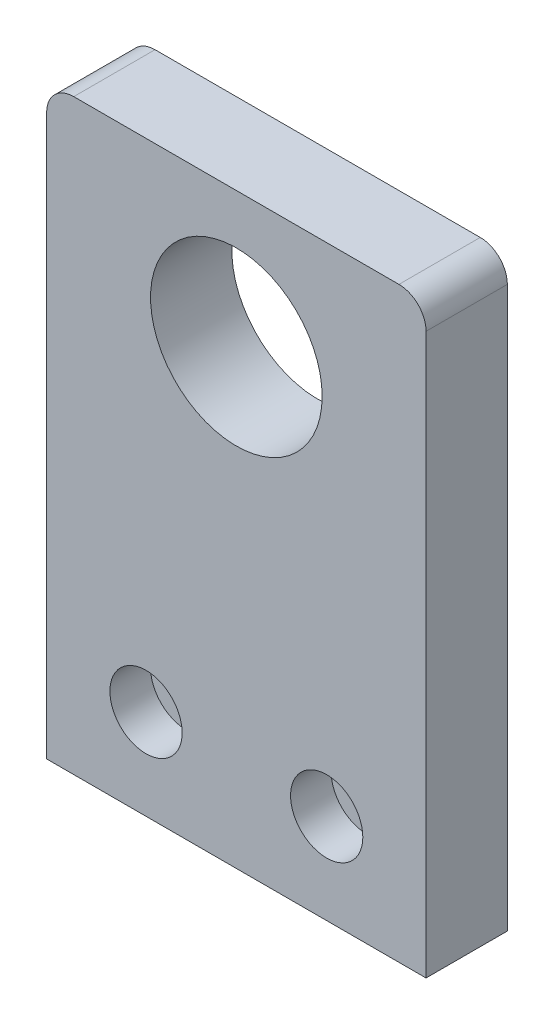
SolidWorks part; units mm, degrees
material "AISI 1035 Acero (SS)"
ref_plane "Alzado" through (0, 0, 0) normal (0, 0, 1) x (1, 0, 0)
ref_plane "Planta" through (0, 0, 0) normal (0, 1, 0) x (1, 0, 0)
ref_plane "Vista lateral" through (0, 0, 0) normal (1, 0, 0) x (0, 0, -1)
sketch "Croquis1" plane through (0, 0, 0) normal (0, 0, 1) x (1, 0, 0)
  line L1 (-18, 32.5) -> (18, 32.5)
  line L2 (-21, 29.5) -> (-21, -32.5)
  line L3 (-21, -32.5) -> (21, -32.5)
  line L4 (21, 29.5) -> (21, -32.5)
  line L5 (-21, 32.5) -> (21, -32.5) construction
  line L6 (-21, -32.5) -> (21, 32.5) construction
  arc A0 (18, 32.5) -> (21, 29.5) centre (18, 29.5) cw
  arc A1 (-18, 32.5) -> (-21, 29.5) centre (-18, 29.5) ccw
  circle A2 centre (0, 17.5) radius 9.5
  circle A3 centre (10, -22.5) radius 2
  circle A4 centre (-10, -22.5) radius 2
  point P0 (0, 0)
  dimension "D3" = 3
  dimension "D4" = 15
  dimension "D5" = 19
  dimension "D6" = 10
  dimension "D7" = 20
  dimension "D1" = 65
  dimension "D2" = 42
  dimension "D8" = 10
extrude "Saliente-Extruir1" add sketch "Croquis1" along normal blind 9
sketch "Croquis2" plane through (0, 0, 9) normal (0, 0, 1) x (1, 0, 0)
  circle A0 centre (-10, -22.5) radius 4
  circle A1 centre (10, -22.5) radius 4
extrude "Cortar-Extruir1" cut sketch "Croquis2" against normal blind 4.5
